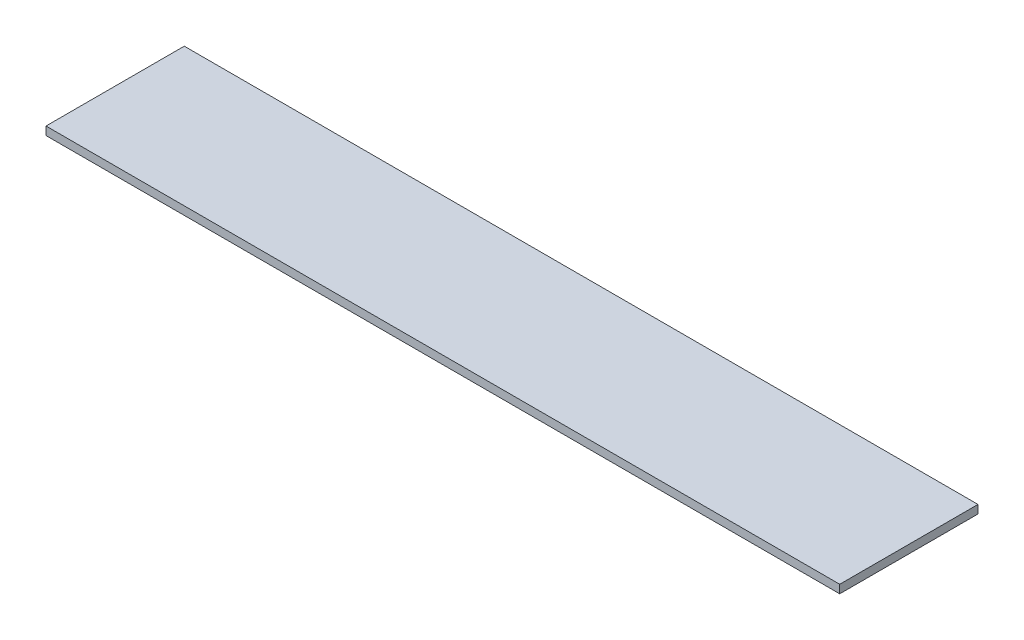
SolidWorks part; units mm, degrees
material "Acrílico (Impacto medio-alto)"
ref_plane "Alzado" through (0, 0, 0) normal (0, 0, 1) x (1, 0, 0)
ref_plane "Planta" through (0, 0, 0) normal (0, 1, 0) x (1, 0, 0)
ref_plane "Vista lateral" through (0, 0, 0) normal (1, 0, 0) x (0, 0, -1)
sketch "Sketch1" plane through (0, 0, 0) normal (0, 1, 0) x (1, 0, 0)
  line L1 (-143.5, -25) -> (143.5, -25)
  line L2 (-143.5, -25) -> (-143.5, 25)
  line L3 (-143.5, 25) -> (143.5, 25)
  line L4 (143.5, -25) -> (143.5, 25)
  line L5 (-143.5, -25) -> (143.5, 25) construction
  line L6 (-143.5, 25) -> (143.5, -25) construction
  point P0 (0, 0)
  dimension "D1" = 50
  dimension "D2" = 287
extrude "Boss-Extrude1" add sketch "Sketch1" along normal blind 3
